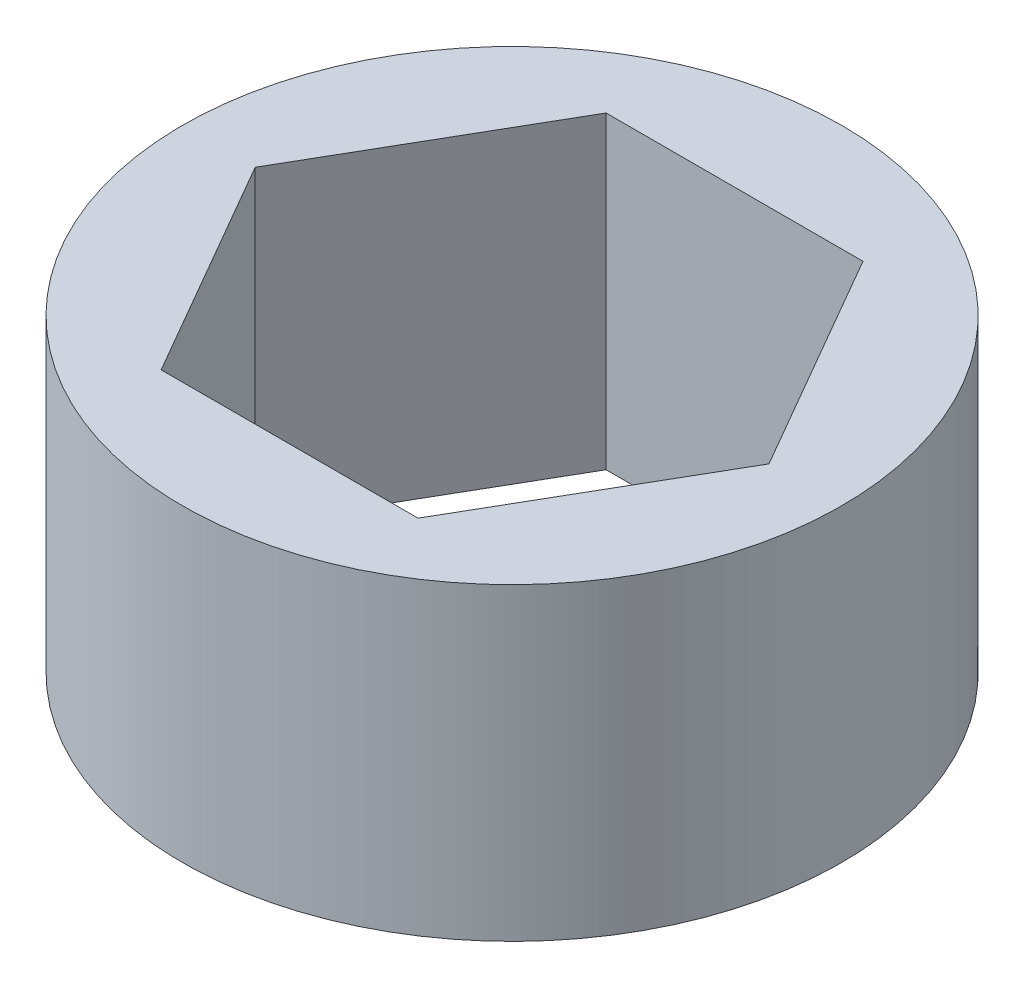
SolidWorks part; units mm, degrees
ref_plane "Front Plane" through (0, 0, 0) normal (0, 0, 1) x (1, 0, 0)
ref_plane "Top Plane" through (0, 0, 0) normal (0, 1, 0) x (1, 0, 0)
ref_plane "Right Plane" through (0, 0, 0) normal (1, 0, 0) x (0, 0, -1)
sketch "Sketch1" plane through (0, 0, 0) normal (0, 1, 0) x (1, 0, 0)
  line L1 (7.9189, 0) -> (3.9595, 6.858)
  line L2 (3.9595, 6.858) -> (-3.9595, 6.858)
  line L3 (-3.9595, 6.858) -> (-7.9189, 0)
  line L4 (-7.9189, 0) -> (-3.9595, -6.858)
  line L5 (-3.9595, -6.858) -> (3.9595, -6.858)
  line L6 (3.9595, -6.858) -> (7.9189, 0)
  circle A0 centre (0, 0) radius 6.858 construction
  circle A1 centre (0, 0) radius 10.16
  dimension "D2" = 20.32
  dimension "D1" = 13.716
extrude "Boss-Extrude1" add sketch "Sketch1" along normal blind 9.525
